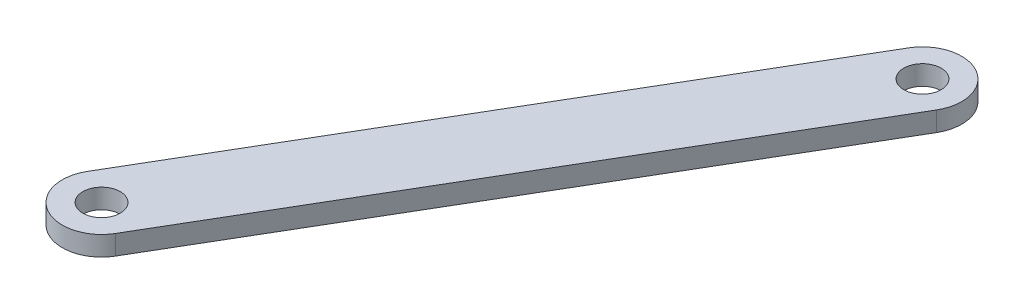
SolidWorks part; units mm, degrees
material "Cedro"
ref_plane "Alzado" through (0, 0, 0) normal (0, 0, 1) x (1, 0, 0)
ref_plane "Planta" through (0, 0, 0) normal (0, 1, 0) x (1, 0, 0)
ref_plane "Vista lateral" through (0, 0, 0) normal (1, 0, 0) x (0, 0, -1)
sketch "Croquis1" plane through (0, 0, 0) normal (0, 1, 0) x (1, 0, 0)
  line L0 (2.7441, 395.2665) -> (-229.13, 0) construction
  line L3 (28.6203, 380.0868) -> (-203.2538, -15.1797)
  line L4 (-23.1321, 410.4462) -> (-255.0062, 15.1797)
  arc A3 (28.6203, 380.0868) -> (-23.1321, 410.4462) centre (2.7441, 395.2665) ccw
  arc A4 (-255.0062, 15.1797) -> (-203.2538, -15.1797) centre (-229.13, 0) ccw
  point P2 (0, 0)
  point P4 (-113.193, 197.6333)
  dimension "D2" = 30
  dimension "D1" = 231.8741
extrude "Saliente-Extruir1" add sketch "Croquis1" along normal blind 15
sketch "Croquis3" plane through (0, 15, 0) normal (0, 1, 0) x (1, 0, 0)
  circle A0 centre (-229.13, 0) radius 14.29
  circle A1 centre (2.7441, 395.2665) radius 14.29
  dimension "D1" = 28.58
  dimension "D2" = 28.58
extrude "Cortar-Extruir2" cut sketch "Croquis3" against normal through all
